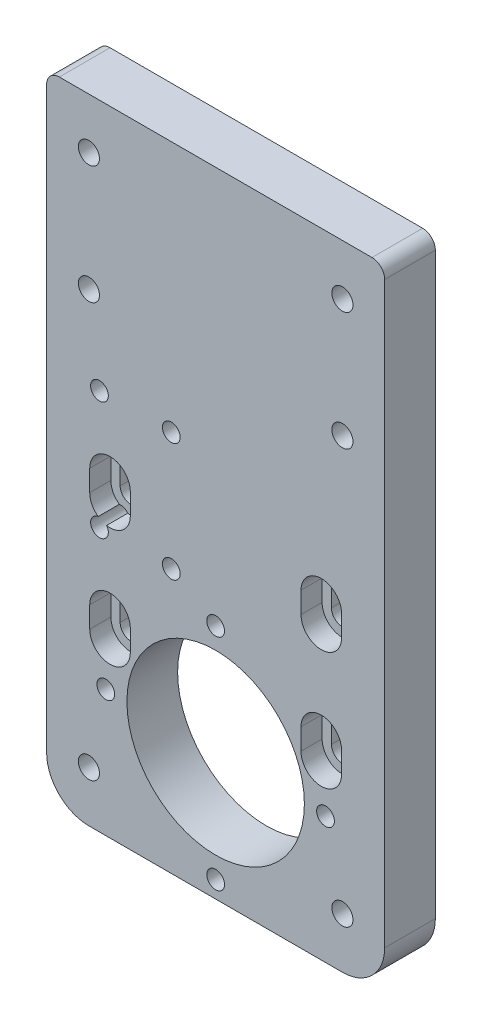
SolidWorks part; units mm, degrees
ref_plane "前视基准面" through (0, 0, 0) normal (0, 0, 1) x (1, 0, 0)
ref_plane "上视基准面" through (0, 0, 0) normal (0, 1, 0) x (1, 0, 0)
ref_plane "右视基准面" through (0, 0, 0) normal (1, 0, 0) x (0, 0, -1)
sketch "草图6" plane through (0, 0, 0) normal (0, 0, 1) x (1, 0, 0)
  line L1 (0, 0) -> (80, 0)
  line L2 (0, 0) -> (0, 150)
  line L3 (0, 150) -> (80, 150)
  line L4 (80, 0) -> (80, 150)
  dimension "D1" = 80
  dimension "D2" = 150
extrude "凸台-拉伸1" add sketch "草图6" along normal blind 12
ref_plane "基准面2" through (40, 0, 0) normal (-1, 0, 0) x (0, 0, 1)
sketch "草图8" plane through (0, 0, 12) normal (0, 0, 1) x (1, 0, 0)
  line L0 (40, 6.6) -> (40, -6.6) construction
  line L1 (0, 0) -> (80, 0) construction
  circle A0 centre (40, 30) radius 21
  dimension "D2" = 42
  dimension "D1" = 30
extrude "切除-拉伸1" cut sketch "草图8" against normal through all
fillet "圆角1" radius 10 2 edges at (0, 0, 6) (80, 0, 6)
hole_wizard "M5 螺纹孔1" positions "草图10" profile "草图9" tap size "M5" standard "GB" end condition through all
sketch "草图10" plane through (0, 0, 12) normal (0, 0, 1) x (1, 0, 0)
  line L0 (40, 6.6) -> (40, -6.6) construction
  circle A0 centre (40, 30) radius 21 construction
  point P0 (40, 56)
  dimension "D1" = 26
sketch "草图9" plane through (40, 56, 12) normal (1, 0, 0) x (0, -1, 0)
  line L0 (0, 0) -> (0, 12)
  line L1 (0, 12) -> (2.1, 12)
  line L2 (2.1, 12) -> (2.1, 0)
  line L5 (2.1, 0) -> (0, 0)
  line L11 (0, -6.35) -> (0, 107.95) construction
  dimension "通孔螺纹孔钻头直径" = 4.2
  dimension "通孔螺纹孔钻头深度" = 12
cosmetic thread "孔螺蚊线1" parameters "D2"=5
pattern_circular "阵列(圆周)1" count 4 every 90 about axis through (40, 30, 0) along (0, 0, 1) of "M5 螺纹孔1"
sketch "草图11" plane through (0, 0, 12) normal (0, 0, 1) x (1, 0, 0)
  line L0 (65, 68.4141) -> (65, 73.4141) construction
  line L1 (62.4, 68.4141) -> (62.4, 73.4141)
  line L2 (67.6, 68.4141) -> (67.6, 73.4141)
  arc A0 (62.4, 68.4141) -> (67.6, 68.4141) centre (65, 68.4141) ccw
  arc A1 (67.6, 73.4141) -> (62.4, 73.4141) centre (65, 73.4141) ccw
  point P2 (65, 70.9141)
  dimension "D1" = 2.6
  dimension "D2" = 5
extrude "切除-拉伸2" cut sketch "草图11" against normal through all
sketch "草图12" plane through (0, 0, 12) normal (0, 0, 1) x (1, 0, 0)
  line L0 (65, 68.4141) -> (65, 73.4141) construction
  line L1 (60.2, 68.4141) -> (60.2, 73.4141)
  line L2 (69.8, 68.4141) -> (69.8, 73.4141)
  arc A0 (60.2, 68.4141) -> (69.8, 68.4141) centre (65, 68.4141) ccw
  arc A1 (69.8, 73.4141) -> (60.2, 73.4141) centre (65, 73.4141) ccw
  point P2 (65, 70.9141)
  dimension "D2" = 4.8
  dimension "D1" = 5
extrude "切除-拉伸3" cut sketch "草图12" against normal blind 5
fillet "圆角2" radius 3 2 edges at (0, 150, 6) (80, 150, 6)
pattern_linear "阵列(线性)1" count 2 spacing 28 along (0, -1, 0) count 2 spacing 50 along (-1, 0, 0) of "切除-拉伸3", "切除-拉伸2"
hole_wizard "M6 螺纹孔1" positions "草图14" profile "草图13" tap size "M6" standard "GB"
sketch "草图14" plane through (0, 0, 12) normal (0, 0, 1) x (1, 0, 0)
  line L0 (10, 0) -> (70, 0) construction
  line L1 (40, 6.6) -> (40, -6.6) construction
  point P0 (70, 12)
  point P2 (70, 110)
  point P4 (70, 138)
  dimension "D1" = 12
  dimension "D2" = 30
  dimension "D3" = 30
  dimension "D4" = 30
  dimension "D5" = 110
  dimension "D6" = 28
sketch "草图13" plane through (70, 12, 12) normal (1, 0, 0) x (0, -1, 0)
  line L0 (0, 0) -> (0, 16.5022)
  line L1 (0, 16.5022) -> (2.5, 15)
  line L2 (2.5, 15) -> (2.5, 0)
  line L5 (2.5, 0) -> (0, 0)
  line L10 (0, 16.5022) -> (-2.5, 15) construction
  line L11 (0, -6.35) -> (0, 107.95) construction
  dimension "螺纹孔钻头直径" = 5
  dimension "螺纹孔钻头深度" = 15
  dimension "导头角度" = 118
cosmetic thread "孔螺蚊线2" parameters "D1"=12, "D2"=6
cosmetic thread "孔螺蚊线3" parameters "D1"=12, "D2"=6
cosmetic thread "孔螺蚊线4" parameters "D1"=12, "D2"=6
mirror "镜向1" about plane through (40, 0, 0) normal (-1, 0, 0) of "M6 螺纹孔1"
hole_wizard "M5 螺纹孔2" positions "草图16" profile "草图15" tap size "M5" standard "GB" end condition through all
sketch "草图16" plane through (0, 0, 0) normal (0, 0, -1) x (-1, 0, 0)
  point P0 (-12.5, 62.4356)
  point P2 (-29.5, 62.4356)
  point P4 (-29.5, 90.4356)
  point P6 (-12.5, 90.4356)
sketch "草图15" plane through (12.5, 62.4356, 0) normal (1, 0, 0) x (0, 1, 0)
  line L0 (0, 0) -> (0, 12)
  line L1 (0, 12) -> (2.1, 12)
  line L2 (2.1, 12) -> (2.1, 0)
  line L5 (2.1, 0) -> (0, 0)
  line L11 (0, -6.35) -> (0, 107.95) construction
  dimension "通孔螺纹孔钻头直径" = 4.2
  dimension "通孔螺纹孔钻头深度" = 12
cosmetic thread "孔螺蚊线5" parameters "D2"=5
cosmetic thread "孔螺蚊线6" parameters "D2"=5
cosmetic thread "孔螺蚊线7" parameters "D2"=5
cosmetic thread "孔螺蚊线8" parameters "D2"=5
